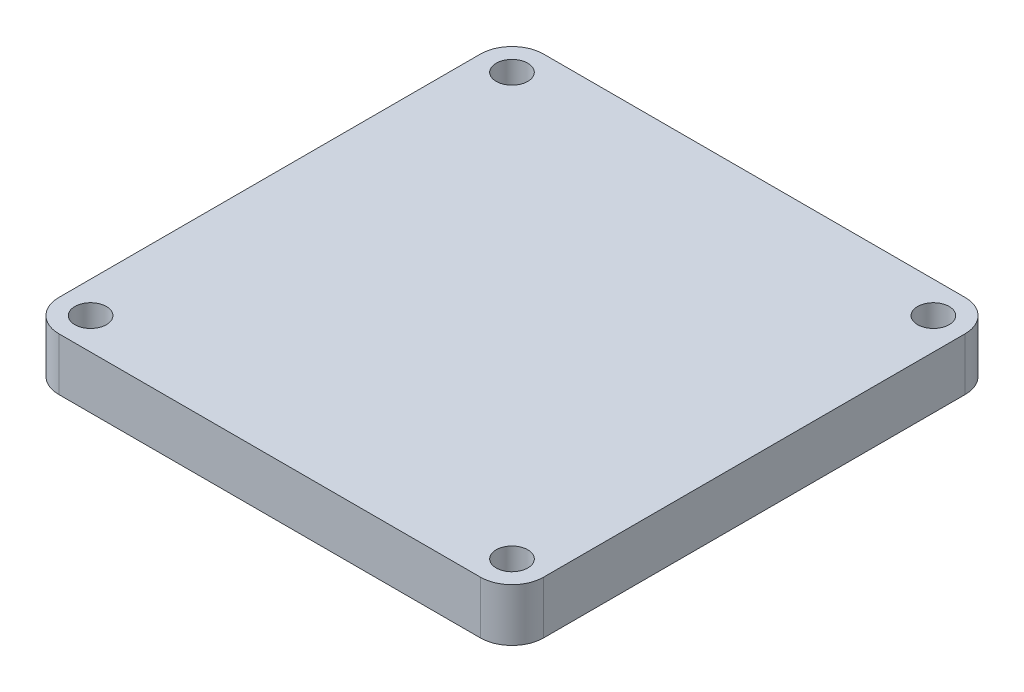
SolidWorks part; units mm, degrees
ref_plane "Front Plane" through (0, 0, 0) normal (0, 0, 1) x (1, 0, 0)
ref_plane "Top Plane" through (0, 0, 0) normal (0, 1, 0) x (1, 0, 0)
ref_plane "Right Plane" through (0, 0, 0) normal (1, 0, 0) x (0, 0, -1)
sketch "Sketch1" plane through (0, 0, 0) normal (0, 1, 0) x (1, 0, 0)
  line L0 (-22.1213, 22.1213) -> (-20, 20) construction
  line L1 (20, -23) -> (-20, -23)
  line L2 (23, -20) -> (23, 20)
  line L3 (20, 23) -> (-20, 23)
  line L4 (-23, -20) -> (-23, 20)
  line L5 (23, -23) -> (-23, 23) construction
  line L6 (23, 23) -> (-23, -23) construction
  line L7 (0, -50) -> (0, 50) construction
  line L8 (50, 0) -> (-50, 0) construction
  arc A0 (-20, -23) -> (-23, -20) centre (-20, -20) cw
  arc A1 (20, -23) -> (23, -20) centre (20, -20) ccw
  arc A2 (23, 20) -> (20, 23) centre (20, 20) ccw
  arc A3 (-20, 23) -> (-23, 20) centre (-20, 20) ccw
  circle A4 centre (-20, 20) radius 1.5
  circle A5 centre (-20, -20) radius 1.5
  circle A6 centre (20, -20) radius 1.5
  circle A7 centre (20, 20) radius 1.5
  point P1 (0, 0)
  point P23 (0, 0)
  point P26 (0, 0)
  dimension "D3" = 3
  dimension "D1" = 46
  dimension "D2" = 46
extrude "Mount_Plate" add sketch "Sketch1" along normal blind 5
sketch "Sketch2" plane through (0, 0, 0) normal (0, 0, 1) x (1, 0, 0)
  line L0 (-1.59, 0) -> (1.59, 0) construction
  line L1 (-20, 0) -> (20, 0) construction
  line L2 (1.59, 0) -> (1.59, -3)
  line L3 (1.59, -3) -> (4.59, 0)
  line L5 (-1.59, 0) -> (-6.59, 0)
  line L6 (-1.59, 0) -> (-1.59, -44.466)
  line L7 (-1.59, -44.466) -> (-6.59, -44.466)
  line L8 (-6.59, 0) -> (-6.59, -44.466)
  point P6 (0, 0)
  dimension "D1" = 3
  dimension "D2" = 3
  dimension "D3" = 5
